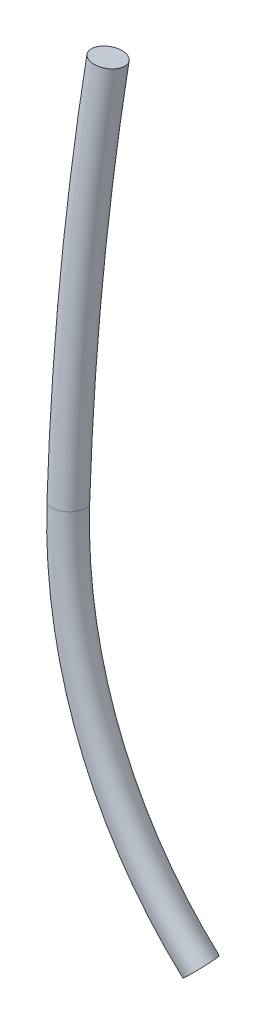
SolidWorks part; units mm, degrees
ref_plane "Front" through (0, 0, 0) normal (0, 0, 1) x (1, 0, 0)
ref_plane "Top" through (0, 0, 0) normal (0, 1, 0) x (1, 0, 0)
ref_plane "Right" through (0, 0, 0) normal (1, 0, 0) x (0, 0, -1)
ref_plane "Plane2" through (-3580.5932, -2177.7408, -17147.8098) normal (0.2028, 0.1234, 0.9714) x (0.9792, -0.0239, -0.2014)
sketch "Sketch2" plane through (-3580.5932, -2177.7408, -17147.8098) normal (0.2028, 0.1234, 0.9714) x (0.9792, -0.0239, -0.2014)
  line L0 (4807.0529, -1813.3269) -> (5246.3362, -2261.9953) construction
  line L1 (4300.4551, 493.4808) -> (4240.8571, -711.9621) construction
  arc A0 (4300.4551, 493.4808) -> (4315.3238, -724.8575) centre (14183.8514, 4.8386) ccw
  arc A1 (4315.3238, -724.8575) -> (4807.0529, -1813.3269) centre (6049.7645, -596.6099) ccw
  spline S0 degree 3 poles (3691.142, 750.8449) (5320.2811, 1053.6848) (5089.1782, -267.1138) (6243.1104, -1070.8819) (7321.3585, -1075.3981) (8126.2332, -113.4873) (7841.5131, 956.3678) (7422.6133, 1843.4545) (6481.582, 2314.1301) (5453.0671, 2242.8018) (4520.4901, 1461.023) (4147.2821, 109.8255) (4335.7494, -1425.347) (5425.942, -2467.4809) (6814.9555, -2680.4589) (8153.1997, -2540.7786) (9645.892, -1568.5209) (10511.6421, -320.5532) (10064.8444, 1941.6453) (9528.0533, 3646.5059) (8044.2967, 4839.093) (6524.2901, 5497.5097) (5137.3921, 5734.6576) (2773.3708, 6056.6347) (809.6596, 5563.4383) (-60.3719, 5073.6446) (-1417.2487, 4257.0828) (-2635.5011, 2737.5571) (-3448.4302, 1027.1053) (-3196.0431, -848.3422) (-1053.0964, -1940.9834) (-18.2647, -2451.4339) (1066.987, -3007.5902) knots -0.035852 -0.035852 -0.035852 -0.035852 0.012418 0.026176 0.053223 0.077498 0.099256 0.122387 0.140197 0.165808 0.187601 0.21914 0.254189 0.284814 0.311917 0.350124 0.381709 0.440659 0.47622 0.524804 0.564919 0.59506 0.63529 0.679111 0.741875 0.781701 0.810098 0.866605 0.901783 0.935896 0.978749 1.044562 1.044562 1.044562 1.044562 only from (5325.3259, -42.5334) to (-717.0572, -2104.3583) construction
  dimension "D1" = 1219.2
  dimension "D2" = 1219.2
sketch "Sketch3" plane through (32.9232, 697.9629, -95.5146) normal (-0.0467, -0.9897, 0.1354) x (0.9989, -0.0463, 0.0063)
  circle A0 centre (597.3624, -18151.9646) radius 50.8
sweep "Sweep1" add profiles "Sketch3" path "Sketch2"
